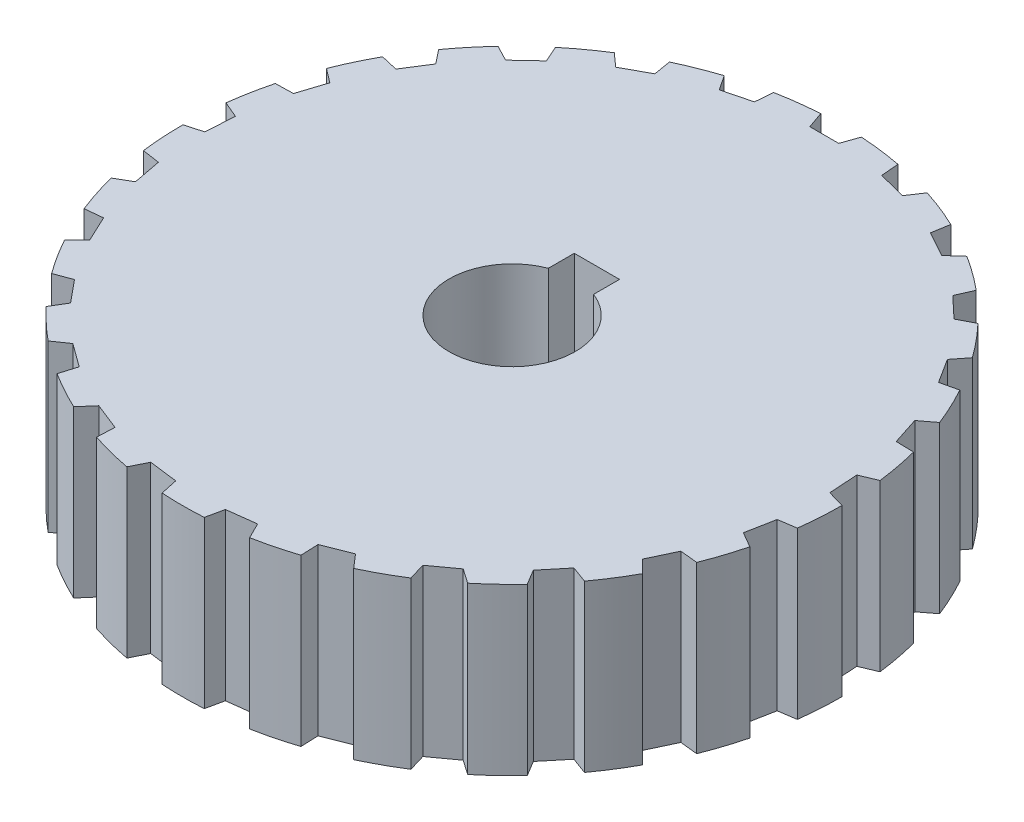
SolidWorks part; units mm, degrees
ref_plane "Front Plane" through (0, 0, 0) normal (0, 0, 1) x (1, 0, 0)
ref_plane "Top Plane" through (0, 0, 0) normal (0, 1, 0) x (1, 0, 0)
ref_plane "Right Plane" through (0, 0, 0) normal (1, 0, 0) x (0, 0, -1)
sketch "Sketch5" plane through (0, 0, 0) normal (0, 1, 0) x (1, 0, 0)
  circle A0 centre (0, 0) radius 37.8968
extrude "Boss-Extrude2" add sketch "Sketch5" along normal blind 19.05
sketch "Sketch8" plane through (0, 19.05, 0) normal (0, 1, 0) x (1, 0, 0)
  line L0 (0, 37.8968) -> (2.36, 37.8968)
  line L1 (0, 37.8968) -> (-2.36, 37.8968)
  line L5 (0, 35.8968) -> (-1.66, 35.8968)
  line L6 (0, 35.8968) -> (1.66, 35.8968)
  line L7 (-2.36, 37.8968) -> (-1.66, 35.8968)
  line L8 (2.36, 37.8968) -> (1.66, 35.8968)
  point P0 (0, 37.8968)
  point P2 (0, 38.1)
  point P3 (0, 37.8968)
  dimension "D1" = 1.66
  dimension "D2" = 1.66
  dimension "D3" = 2
  dimension "D4" = 2.36
  dimension "D5" = 2.36
extrude "Cut-Extrude1" cut sketch "Sketch8" against normal blind 22.05
pattern_circular "CirPattern1" count 25 over 360 about axis through (0, 0, 0) along (0, 1, 0) of "Cut-Extrude1"
sketch "Sketch9" plane through (0, 19.05, 0) normal (0, 1, 0) x (1, 0, 0)
  line L0 (0, 7.25) -> (2.6, 7.25)
  line L1 (0, 7.25) -> (-2.6, 7.25)
  line L2 (-2.6, 7.25) -> (-2.6, 6.7678)
  line L3 (2.6, 7.25) -> (2.6, 6.7678)
  line L4 (-2.6, 7.25) -> (-2.6, 9.75)
  line L5 (-2.6, 9.75) -> (2.6, 9.75)
  line L6 (2.6, 9.75) -> (2.6, 7.25)
  circle A0 centre (0, 0) radius 7.25
extrude "Cut-Extrude2" cut sketch "Sketch9" against normal blind 25.4 contours A0 | L6 L5 L4 L1 L0 | A0 L1 L2 | A0 L3 L0
